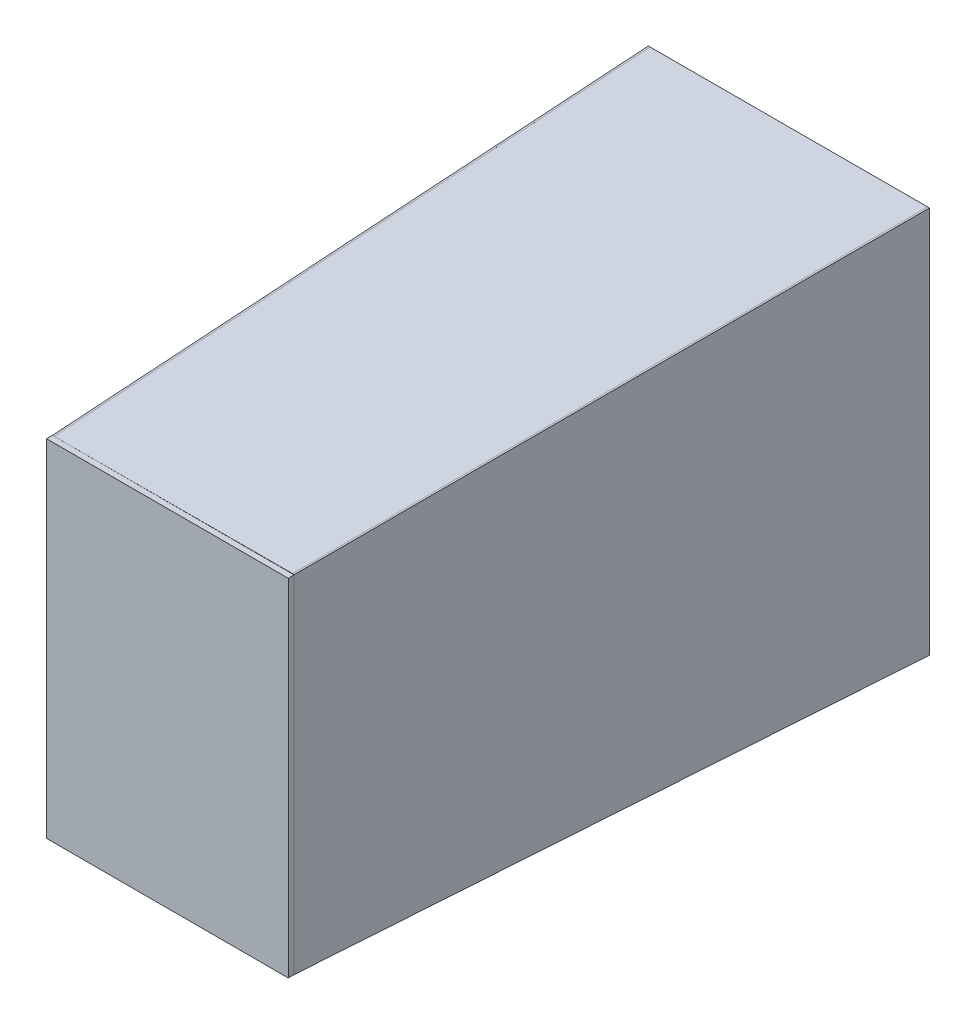
SolidWorks part; units mm, degrees
ref_plane "Front Plane" through (0, 0, 0) normal (0, 0, 1) x (1, 0, 0)
ref_plane "Top Plane" through (0, 0, 0) normal (0, 1, 0) x (1, 0, 0)
ref_plane "Right Plane" through (0, 0, 0) normal (1, 0, 0) x (0, 0, -1)
sketch "Sketch1" plane through (0, 0, 0) normal (0, 1, 0) x (1, 0, 0)
  line L0 (0, 0) -> (209.55, 0)
  line L1 (228.6516, 547.6875) -> (211.0875, -1.5875)
  line L3 (-1.5375, -1.5875) -> (211.0875, -1.5875)
  line L4 (-19.1016, 547.6875) -> (-1.5375, -1.5875)
  line L5 (227.0633, 547.6875) -> (209.55, 0)
  line L6 (-17.5133, 547.6875) -> (0, 0)
  line L7 (228.6516, 547.6875) -> (227.0633, 547.6875)
  line L8 (227.0125, 546.1) -> (-17.4625, 546.1) construction
  line L9 (227.0125, 546.1) -> (209.55, 0) construction
  line L10 (-17.4625, 546.1) -> (0, 0) construction
  line L11 (-17.5133, 547.6875) -> (-19.1016, 547.6875)
  line L12 (228.6516, 547.6875) -> (-19.1016, 547.6875) construction
  point P11 (0, 0)
  dimension "D1" = 1.5875
extrude "Boss-Extrude1" add sketch "Sketch1" against normal blind 339.725
sketch "Sketch3" plane through (210.9226, 0, 6.7446) normal (0.9995, 0, 0.032) x (0.032, 0, -0.9995)
  line L0 (5.1598, -169.8625) -> (554.7155, -169.8625) construction
  line L1 (5.1598, -339.725) -> (5.1598, 0) construction
  line L2 (554.7155, -339.725) -> (554.7155, 0) construction
  line L3 (5.2019, -17.4612) -> (554.7155, 0)
  line L4 (5.1598, -322.2625) -> (554.7155, -339.725)
  line L5 (5.2102, -19.0492) -> (554.7155, -1.5883)
  line L6 (5.1598, -323.8508) -> (554.7155, -341.3133)
  line L7 (5.2102, -19.0492) -> (5.2019, -17.4612)
  line L8 (5.1598, -17.4625) -> (554.7155, 0) construction
  line L10 (554.7155, -339.725) -> (554.7155, -341.3133)
  line L11 (5.1093, -323.8492) -> (554.6651, -341.3117) construction
  line L12 (5.1598, -322.2625) -> (5.1598, -323.8508)
  line L13 (5.2102, -19.0492) -> (554.7659, -1.5867) construction
  line L14 (554.7155, 0) -> (554.7155, -1.5883)
  dimension "D1" = 1.5875
extrude "Boss-Extrude2" add sketch "Sketch3" against normal up to surface (248.1335 mm away)
sketch "Sketch5" plane through (210.9226, 0, 6.7446) normal (0.9995, 0, 0.032) x (0.032, 0, -0.9995)
  line L0 (5.1598, -169.8625) -> (246.8517, -169.8625) construction
  line L1 (5.1598, -339.725) -> (5.1598, 0) construction
  line L3 (5.1598, -322.2638) -> (554.7155, -341.3133)
  line L4 (554.7155, -341.3133) -> (-187.5148, -341.3133)
  line L5 (-187.5148, -341.3133) -> (5.1598, -322.2638)
  line L8 (5.1598, -17.4612) -> (-85.4922, -17.4612)
  line L9 (-85.4922, -17.4612) -> (-85.4922, 58.9634)
  line L10 (-85.4922, 58.9634) -> (554.7155, 0)
  line L11 (554.7155, 0) -> (5.1598, -17.4612)
extrude "Cut-Extrude4" cut sketch "Sketch5" against normal through all
sketch "Sketch6" plane through (0, 0, 0) normal (0, 1, 0) x (1, 0, 0)
  line L0 (-1.7552, 5.2185) -> (295.7687, 5.2185)
  line L1 (295.7687, 5.2185) -> (295.7687, -74.4004)
  line L2 (295.7687, -74.4004) -> (-24.6233, -74.4004)
  line L3 (-24.6233, -74.4004) -> (-1.7552, 5.2185)
  line L5 (-64.0152, 547.6875) -> (312.498, 547.6875)
  line L6 (-64.0152, 547.6875) -> (-64.0152, 601.2941)
  line L7 (-64.0152, 601.2941) -> (312.498, 601.2941)
  line L8 (312.498, 547.6875) -> (312.498, 601.2941)
extrude "Cut-Extrude8" cut sketch "Sketch6" against normal through all
sketch "Sketch7" plane through (0, 0, 0) normal (0, 0, 1) x (1, 0, 0)
  line L1 (-1.7552, -17.4612) -> (211.3052, -17.4612)
  line L2 (-1.7552, -17.4612) -> (-1.7552, -322.4999)
  line L3 (-1.7552, -322.4999) -> (211.3052, -322.4999)
  line L4 (211.3052, -17.4612) -> (211.3052, -322.4999)
extrude "Boss-Extrude4" add sketch "Sketch7" against normal blind 5.842
